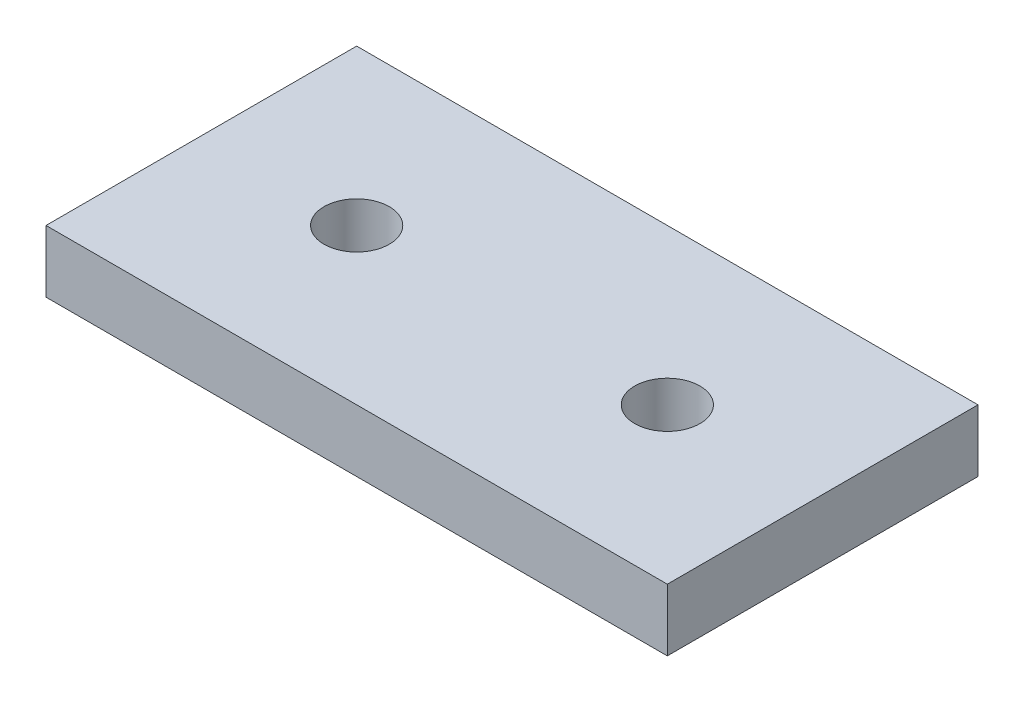
SolidWorks part; units mm, degrees
ref_plane "前视基准面" through (0, 0, 0) normal (0, 0, 1) x (1, 0, 0)
ref_plane "上视基准面" through (0, 0, 0) normal (0, 1, 0) x (1, 0, 0)
ref_plane "右视基准面" through (0, 0, 0) normal (1, 0, 0) x (0, 0, -1)
other "Configuration Table"
sketch "草图1" plane through (0, 0, 0) normal (0, 1, 0) x (1, 0, 0)
  line L1 (-20, 10) -> (20, 10)
  line L2 (-20, 10) -> (-20, -10)
  line L3 (-20, -10) -> (20, -10)
  line L4 (20, 10) -> (20, -10)
  line L5 (-20, 10) -> (20, -10) construction
  line L6 (-20, -10) -> (20, 10) construction
  circle A0 centre (-10, 0) radius 2.1
  circle A1 centre (10, 0) radius 2.1
  point P0 (0, 0)
  dimension "D3" = 4.2
  dimension "D4" = 4.2
  dimension "D1" = 20
  dimension "D2" = 40
  dimension "D5" = 20
  dimension "D6" = 10
  dimension "D7" = 10
  dimension "D8" = 10
extrude "凸台-拉伸1" add sketch "草图1" along normal blind 4
